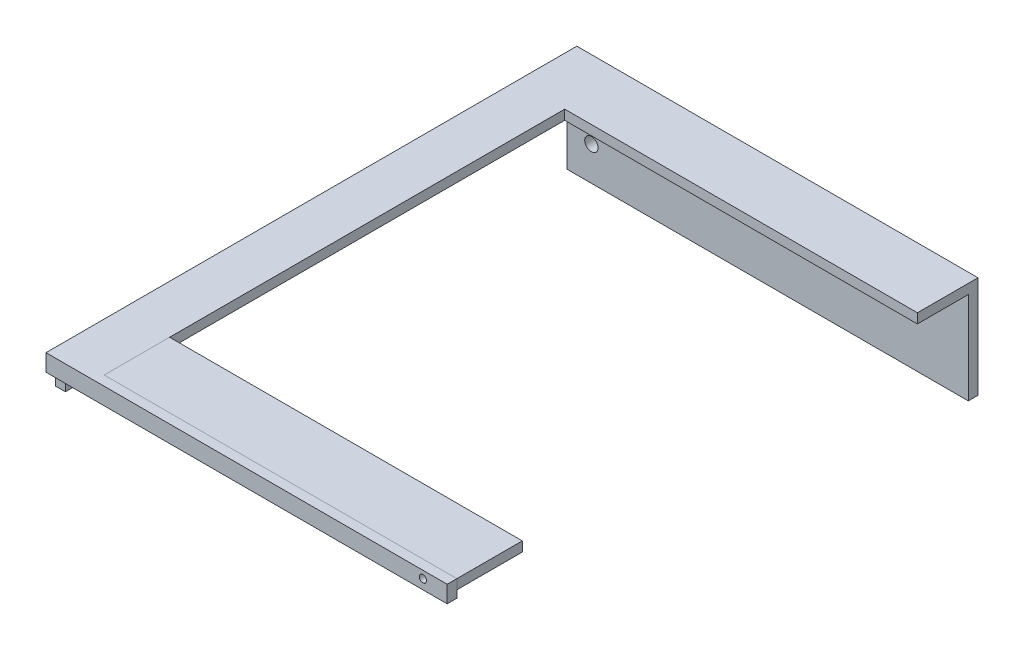
SolidWorks part; units mm, degrees
ref_plane "前视基准面" through (0, 0, 0) normal (0, 0, 1) x (1, 0, 0)
ref_plane "上视基准面" through (0, 0, 0) normal (0, 1, 0) x (1, 0, 0)
ref_plane "右视基准面" through (0, 0, 0) normal (1, 0, 0) x (0, 0, -1)
other "Configuration Table"
sketch "草图1" plane through (0, 0, 0) normal (0, 0, 1) x (1, 0, 0)
  line L1 (0, 0) -> (165.5, 0)
  line L2 (0, 0) -> (0, -38)
  line L3 (0, -38) -> (165.5, -38)
  line L4 (165.5, 0) -> (165.5, -38)
  dimension "D1" = 165.5
  dimension "D2" = 38
extrude "凸台-拉伸1" add sketch "草图1" along normal blind 4
sketch "草图2" plane through (0, 0, 0) normal (0, 1, 0) x (1, 0, 0)
  line L1 (0, 0) -> (20, 0)
  line L2 (0, 0) -> (0, -215)
  line L3 (0, -215) -> (20, -215)
  line L4 (20, 0) -> (20, -215)
  dimension "D1" = 215
  dimension "D2" = 20
extrude "凸台-拉伸2" add sketch "草图2" along normal blind 4
sketch "草图3" plane through (0, 0, 0) normal (-1, 0, 0) x (0, 0, 1)
  line L0 (215, 4) -> (215, 0) construction
  line L1 (4, 0) -> (215, 0)
  line L2 (4, 0) -> (4, -10)
  line L3 (4, -10) -> (215, -10)
  line L4 (215, 0) -> (215, -10)
  dimension "D1" = 10
extrude "凸台-拉伸3" add sketch "草图3" against normal blind 4
sketch "草图4" plane through (0, 0, 0) normal (0, 1, 0) x (1, 0, 0)
  line L0 (165.5, -4) -> (165.5, 0) construction
  line L1 (20, 0) -> (165.5, 0)
  line L2 (20, 0) -> (20, -25)
  line L3 (20, -25) -> (165.5, -25)
  line L4 (165.5, 0) -> (165.5, -25)
  dimension "D1" = 25
extrude "凸台-拉伸4" add sketch "草图4" along normal blind 4
sketch "草图5" plane through (0, 0, 0) normal (0, 0, -1) x (-1, 0, 0)
  line L0 (-165.5, 4) -> (0, 4) construction
  line L1 (-165.5, -38) -> (-165.5, 4) construction
  circle A0 centre (-140.5, -16) radius 1.5
  dimension "D1" = 3
  dimension "D2" = 20
  dimension "D3" = 25
extrude "切除-拉伸1" cut sketch "草图5" against normal blind 4
sketch "草图6" plane through (0, 0, 215) normal (0, 0, 1) x (1, 0, 0)
  line L0 (165.5, -38) -> (165.5, 0) construction
  line L1 (0, 4) -> (165.5, 4)
  line L2 (0, 4) -> (0, -3)
  line L3 (0, -3) -> (165.5, -3)
  line L4 (165.5, 4) -> (165.5, -3)
  dimension "D1" = 7
extrude "凸台-拉伸5" add sketch "草图6" along normal blind 4
sketch "草图7" plane through (0, 4, 0) normal (0, 1, 0) x (1, 0, 0)
  line L0 (165.5, -219) -> (165.5, -215) construction
  line L1 (20, -215) -> (165.5, -215)
  line L2 (20, -215) -> (20, -188)
  line L3 (20, -188) -> (165.5, -188)
  line L4 (165.5, -215) -> (165.5, -188)
  dimension "D1" = 27
extrude "凸台-拉伸6" add sketch "草图7" against normal blind 4 separate body
sketch "草图8" plane through (0, 0, 0) normal (0, 0, -1) x (-1, 0, 0)
  line L0 (0, -38) -> (-165.5, -38) construction
  line L1 (0, 4) -> (0, -38) construction
  circle A0 centre (-10, -24) radius 2.75
  dimension "D1" = 5.5
  dimension "D2" = 14
  dimension "D3" = 10
extrude "切除-拉伸2" cut sketch "草图8" against normal blind 4
sketch "草图9" plane through (0, 0, 219) normal (0, 0, 1) x (1, 0, 0)
  line L0 (165.5, 4) -> (0, 4) construction
  line L1 (165.5, -3) -> (165.5, 4) construction
  circle A0 centre (155.5, 1) radius 1.5
  dimension "D1" = 3
  dimension "D2" = 3
  dimension "D3" = 10
extrude "切除-拉伸3" cut sketch "草图9" against normal blind 20
